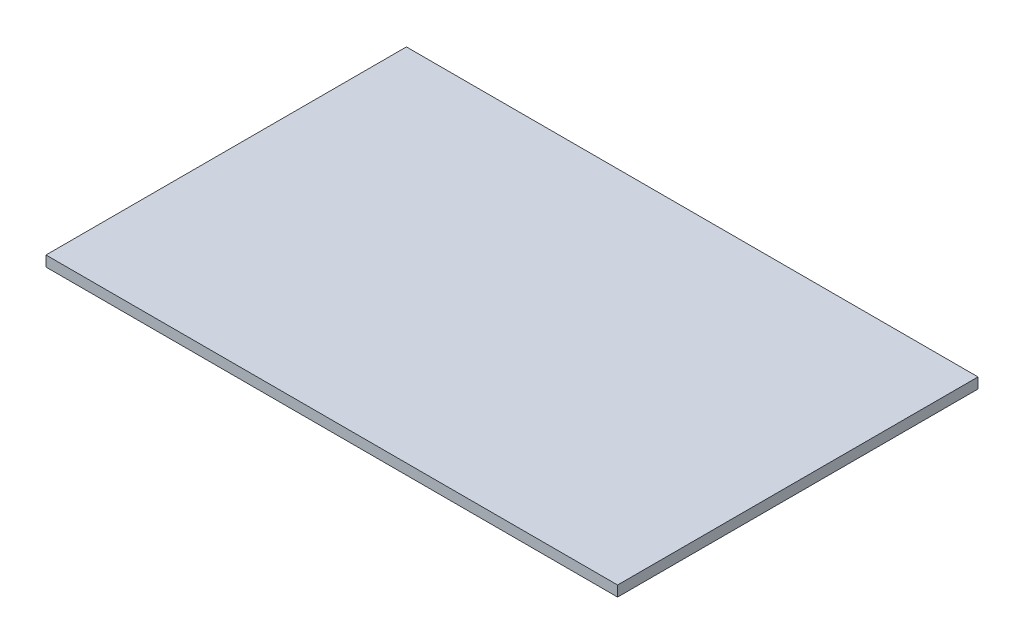
SolidWorks part; units mm, degrees
material "1.0503 (C45)"
ref_plane "Front Plane" through (0, 0, 0) normal (0, 0, 1) x (1, 0, 0)
ref_plane "Top Plane" through (0, 0, 0) normal (0, 1, 0) x (1, 0, 0)
ref_plane "Right Plane" through (0, 0, 0) normal (1, 0, 0) x (0, 0, -1)
sketch "Sketch1" plane through (0, 0, 0) normal (0, 1, 0) x (1, 0, 0)
  line L1 (-27.2, -17.15) -> (27.2, -17.15)
  line L2 (-27.2, -17.15) -> (-27.2, 17.15)
  line L3 (-27.2, 17.15) -> (27.2, 17.15)
  line L4 (27.2, -17.15) -> (27.2, 17.15)
  line L5 (-27.2, -17.15) -> (27.2, 17.15) construction
  line L6 (-27.2, 17.15) -> (27.2, -17.15) construction
  point P0 (0, 0)
  dimension "D1" = 54.4
  dimension "D2" = 34.3
extrude "Boss-Extrude1" add sketch "Sketch1" along normal mid plane 1
